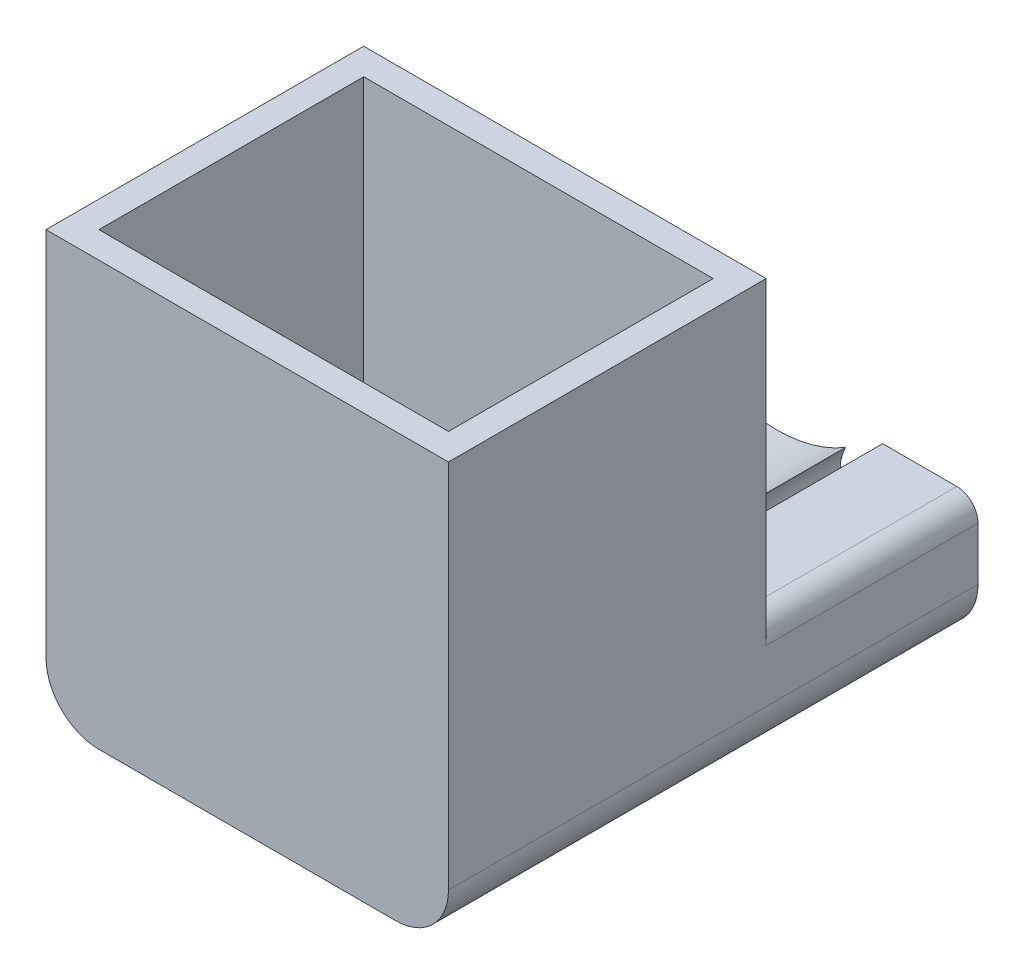
SolidWorks part; units mm, degrees
material "ONYX"
ref_plane "Front Plane" through (0, 0, 0) normal (0, 0, 1) x (1, 0, 0)
ref_plane "Top Plane" through (0, 0, 0) normal (0, 1, 0) x (1, 0, 0)
ref_plane "Right Plane" through (0, 0, 0) normal (1, 0, 0) x (0, 0, -1)
sketch "Sketch1" plane through (0, 0, 0) normal (0, 0, 1) x (1, 0, 0)
  line L0 (0, 19.635) -> (0, -21.1244) construction
  line L1 (-10, -9.1244) -> (-19, -9.1244)
  line L2 (-19, -9.1244) -> (-19, -21.1244)
  line L6 (19, -9.1244) -> (10, -9.1244)
  line L9 (-19, -21.1244) -> (19, -21.1244)
  line L10 (19, -21.1244) -> (19, -9.1244)
  circle A0 centre (0, 0) radius 12.5 construction
  arc A1 (6.5091, -11.1715) -> (10, -9.1244) centre (10, -13.1244) ccw
  arc A2 (-6.5091, -11.1715) -> (-10, -9.1244) centre (-10, -13.1244) cw
  circle A3 centre (0, 11.4164) radius 22.5 construction
  arc A4 (-6.5091, -11.1715) -> (6.5091, -11.1715) centre (0, -0.5) ccw
  circle A5 centre (-10, -13.1244) radius 4 construction
  circle A6 centre (10, -13.1244) radius 4 construction
  dimension "D1" = 25
  dimension "D2" = 8
  dimension "D4" = 45
  dimension "D5" = 12.5
  dimension "D3" = 10
  dimension "D6" = 0.5
  dimension "D7" = 9
  dimension "D8" = 12
  dimension "D9" = 9
extrude "Boss-Extrude1" add sketch "Sketch1" along normal mid plane 20
sketch "Sketch2" plane through (0, 0, 10) normal (0, 0, 1) x (1, 0, 0)
  line L0 (-19, -21.1244) -> (-19, 18.8756)
  line L1 (-19, -21.1244) -> (19, -21.1244)
  line L2 (-19, -21.1244) -> (19, -21.1244) construction
  line L3 (19, -21.1244) -> (19, -9.1244) construction
  line L4 (19, -21.1244) -> (19, 18.8756)
  line L5 (19, 18.8756) -> (-19, 18.8756)
  dimension "D1" = 40
extrude "Boss-Extrude2" add sketch "Sketch2" along normal blind 30
fillet "Fillet1" radius 5 2 edges at (-19, -21.1244, 15) (19, -21.1244, 15)
fillet "Fillet2" radius 2 2 edges at (-19, -9.1244, 0) (19, -9.1244, 0)
sketch "Sketch4" plane through (0, 18.8756, 0) normal (0, 1, 0) x (1, 0, 0)
  line L0 (19, -40) -> (-19, -40) construction
  line L1 (16.5, -37.5) -> (-16.5, -37.5)
  line L2 (16.5, -37.5) -> (16.5, -12.5)
  line L3 (16.5, -12.5) -> (-16.5, -12.5)
  line L4 (-16.5, -37.5) -> (-16.5, -12.5)
  line L5 (16.5, -37.5) -> (-16.5, -12.5) construction
  line L6 (16.5, -12.5) -> (-16.5, -37.5) construction
  line L7 (19, -10) -> (-19, -10) construction
  line L8 (-19, -40) -> (-19, -10) construction
  line L9 (19, -40) -> (19, -10) construction
  point P0 (0, -25)
  dimension "D1" = 2.5
  dimension "D2" = 2.5
  dimension "D3" = 2.5
  dimension "D4" = 2.5
extrude "Cut-Extrude1" cut sketch "Sketch4" against normal blind 35
